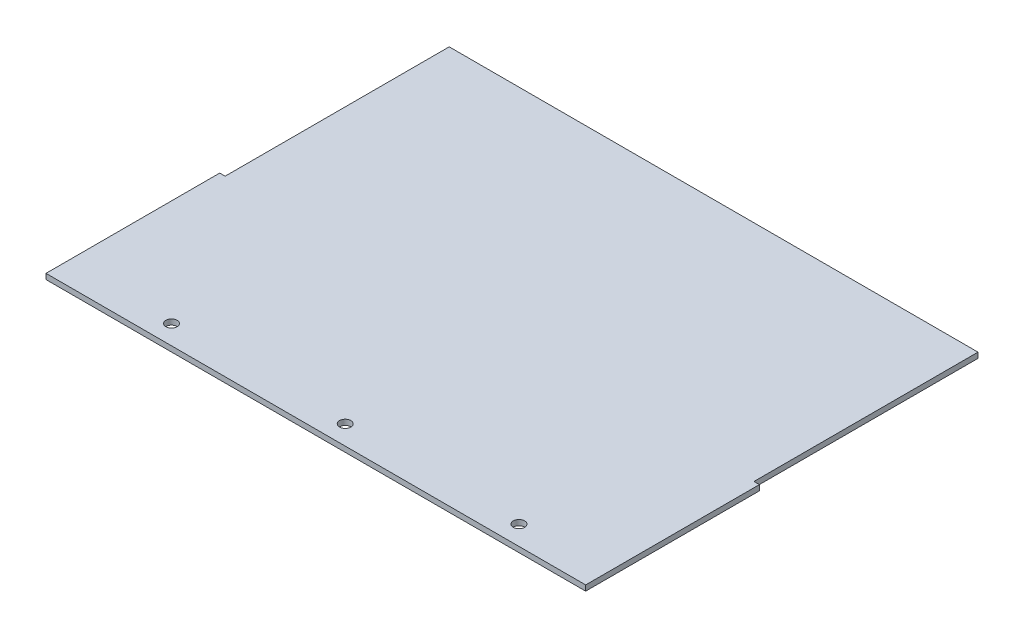
SolidWorks part; units mm, degrees
material "Custom Plastic"
ref_plane "X-Y Datum" through (0, 0, 0) normal (0, 0, 1) x (1, 0, 0)
ref_plane "X-Z Datum" through (0, 0, 0) normal (0, 1, 0) x (1, 0, 0)
ref_plane "Y-Z Datum" through (0, 0, 0) normal (1, 0, 0) x (0, 0, -1)
sketch "Sketch1" plane through (0, 0, 0) normal (0, 0, 1) x (1, 0, 0)
  line L1 (-157.79, -1.5875) -> (157.79, -1.5875)
  line L2 (-157.79, -1.5875) -> (-157.79, 1.5875)
  line L3 (-157.79, 1.5875) -> (157.79, 1.5875)
  line L4 (157.79, -1.5875) -> (157.79, 1.5875)
  line L5 (-157.79, -1.5875) -> (157.79, 1.5875) construction
  line L6 (-157.79, 1.5875) -> (157.79, -1.5875) construction
  point P0 (0, 0)
  dimension "D1" = 315.58
  dimension "D2" = 3.175
extrude "Boss-Extrude1" add sketch "Sketch1" along normal blind 232.6
sketch "Sketch5" plane through (0, 1.5875, 0) normal (0, 1, 0) x (1, 0, 0)
  line L15 (-157.79, 0) -> (-154.615, 0)
  line L16 (-157.79, 0) -> (-157.79, -131)
  line L17 (-157.79, -131) -> (-154.615, -131)
  line L18 (-154.615, 0) -> (-154.615, -131)
  dimension "D3" = 3.175
  dimension "D4" = 131
extrude "Cut-Extrude2" cut sketch "Sketch5" against normal through all and the other way through all
mirror "Mirror1" about plane through (0, 0, 0) normal (1, 0, 0) of "Cut-Extrude2"
sketch "Sketch7" plane through (0, -1.5875, 0) normal (0, -1, 0) x (1, 0, 0)
  line L0 (110.4954, 221.3083) -> (104.4954, 221.3083) construction
  circle A0 centre (107.4954, 221.3083) radius 3.302
  dimension "D1" = 6.604
extrude "Cut-Extrude3" cut sketch "Sketch7" against normal through all
pattern_linear "LPattern1" count 3 spacing 101.6 along (-1, 0, 0) of "Cut-Extrude3"
